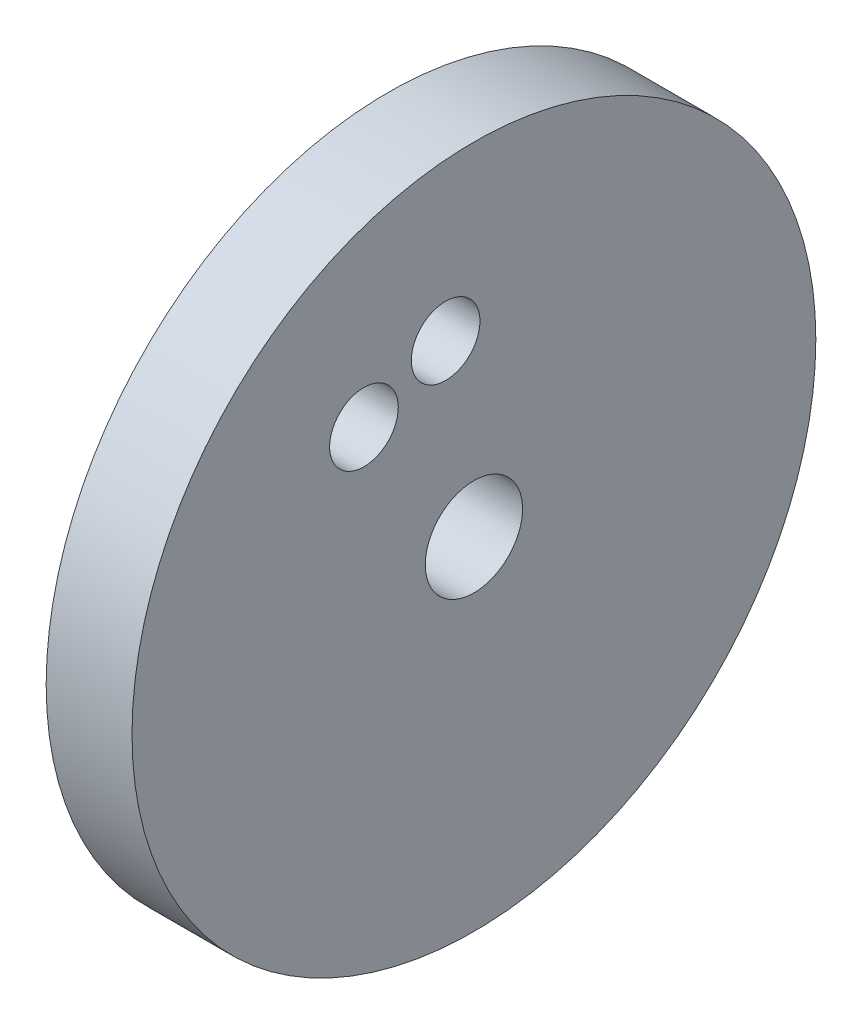
SolidWorks part; units mm, degrees
material "Alumina"
ref_plane "Front Plane" through (0, 0, 0) normal (0, 0, 1) x (1, 0, 0)
ref_plane "Top Plane" through (0, 0, 0) normal (0, 1, 0) x (1, 0, 0)
ref_plane "Right Plane" through (0, 0, 0) normal (1, 0, 0) x (0, 0, -1)
sketch "Axial profile (mm)" plane through (0, 0, 0) normal (0, 0, 1) x (1, 0, 0)
  line L0 (-110, 0) -> (75, 0) construction
  line L1 (73, 3.4) -> (79, 3.4)
  line L2 (79, 3.4) -> (79, 23.9)
  line L3 (79, 23.9) -> (73, 23.9)
  line L4 (73, 23.9) -> (73, 3.4)
revolve "Full revolution" add sketch "Axial profile (mm)" angle 360 about L0
sketch "Sketch2" plane through (0, 0, 0) normal (1, 0, 0) x (0, 0, -1)
  circle A0 centre (-1.9774, 12.8487) radius 2.4
  circle A1 centre (-7.6872, 10.4836) radius 2.4
extrude "Axial holes" cut sketch "Sketch2" against normal through all and the other way through all
